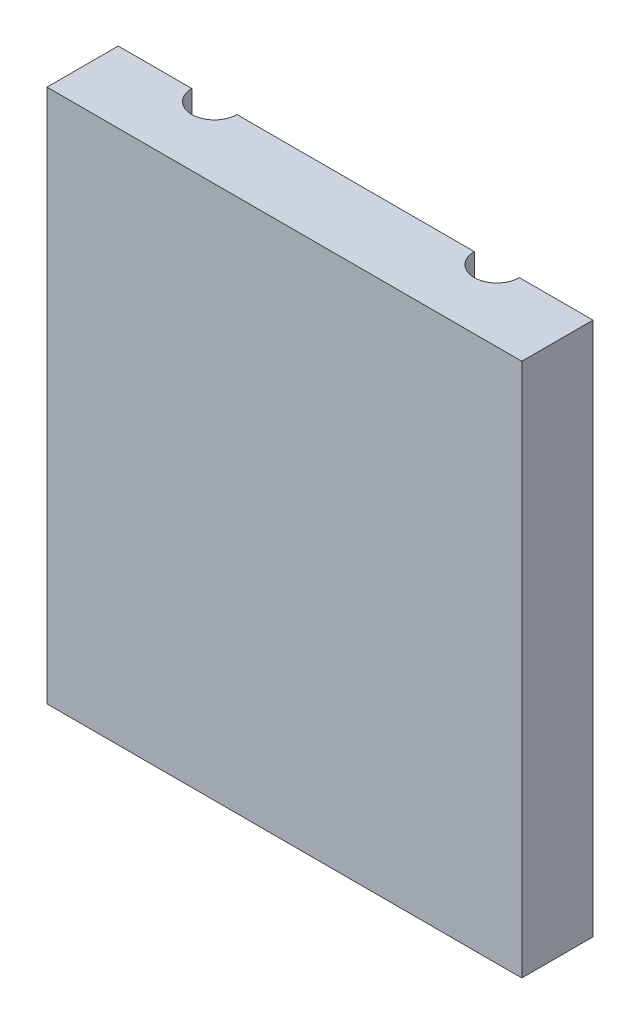
SolidWorks part; units mm, degrees
ref_plane "Front Plane" through (0, 0, 0) normal (0, 0, 1) x (1, 0, 0)
ref_plane "Top Plane" through (0, 0, 0) normal (0, 1, 0) x (1, 0, 0)
ref_plane "Right Plane" through (0, 0, 0) normal (1, 0, 0) x (0, 0, -1)
sketch "Sketch1" plane through (0, 0, 0) normal (0, 0, 1) x (1, 0, 0)
  line L1 (-20, 22.5) -> (20, 22.5)
  line L2 (-20, 22.5) -> (-20, -22.5)
  line L3 (-20, -22.5) -> (20, -22.5)
  line L4 (20, 22.5) -> (20, -22.5)
  line L5 (-20, 22.5) -> (20, -22.5) construction
  line L6 (-20, -22.5) -> (20, 22.5) construction
  point P0 (0, 0)
  dimension "D1" = 40
  dimension "D2" = 45
extrude "Base" add sketch "Sketch1" along normal blind 6
sketch "Sketch2" plane through (0, 22.5, 0) normal (0, 1, 0) x (1, 0, 0)
  line L0 (20, 0) -> (-20, 0) construction
  line L1 (-13.8, 0) -> (-10, 0)
  line L2 (0, 0) -> (0, -6) construction
  line L3 (20, -6) -> (-20, -6) construction
  line L4 (13.8, 0) -> (10, 0)
  arc A0 (-13.8, 0) -> (-10, 0) centre (-11.9, 0) ccw
  arc A1 (13.8, 0) -> (10, 0) centre (11.9, 0) cw
  dimension "D1" = 1.9
  dimension "D2" = 11.9
extrude "Wire Grooves" cut sketch "Sketch2" against normal through all
